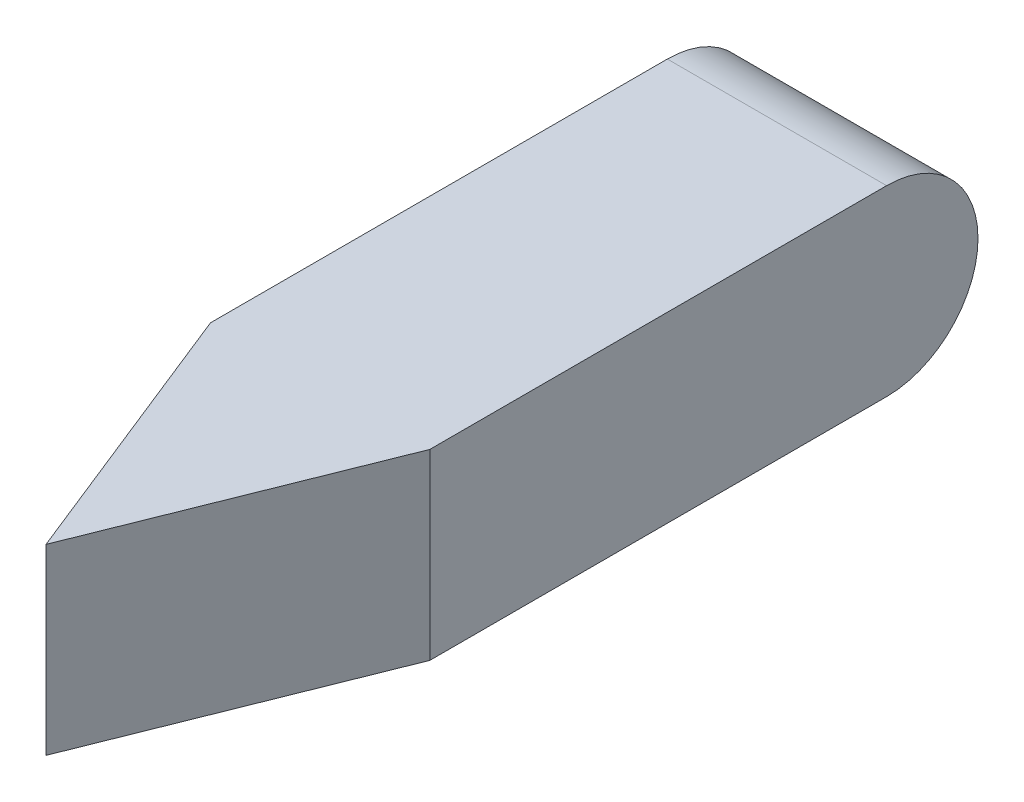
SolidWorks part; units mm, degrees
ref_plane "前视基准面" through (0, 0, 0) normal (0, 0, 1) x (1, 0, 0)
ref_plane "上视基准面" through (0, 0, 0) normal (0, 1, 0) x (1, 0, 0)
ref_plane "右视基准面" through (0, 0, 0) normal (1, 0, 0) x (0, 0, -1)
sketch "草图2" plane through (0, 0, 0) normal (0, 0, 1) x (1, 0, 0)
  line L1 (0, 0) -> (12, 0)
  line L2 (0, 0) -> (0, 10)
  line L3 (0, 10) -> (12, 10)
  line L4 (12, 0) -> (12, 10)
  dimension "D1" = 10
  dimension "D2" = 12
extrude "凸台-拉伸1" add sketch "草图2" along normal blind 45
sketch "草图3" plane through (12, 0, 0) normal (1, 0, 0) x (0, 0, -1)
  line L1 (-45, 10) -> (0, 10) construction
  line L3 (-45, 0) -> (0, 0) construction
  line L4 (0, 0) -> (0, 10) construction
  line L5 (-5, 10) -> (0, 10)
  line L6 (0, 10) -> (0, 0)
  line L7 (0, 0) -> (-5, 0)
  circle A1 centre (-5, 5) radius 5
  line M1 (0, 0) -> (0, 10)
  line M2 (0, 10) -> (-45, 10)
  line M4 (-45, 0) -> (0, 0)
extrude "切除-拉伸1" cut sketch "草图3" against normal blind 65 contours A1 M4 M1 | A1 L6 M2
sketch "草图4" plane through (0, 0, 0) normal (0, -1, 0) x (1, 0, 0)
  line L0 (0, 30) -> (0, 45)
  line L1 (0, 45) -> (0, 5) construction
  line L2 (0, 45) -> (6, 45)
  line L4 (6, 45) -> (12, 45)
  line L6 (12, 45) -> (12, 5) construction
  line L7 (0, 45) -> (12, 45) construction
  line L8 (12, 45) -> (12, 30)
  line L9 (12, 30) -> (6, 45)
  line L10 (0, 30) -> (6, 45)
  line M2 (0, 45) -> (0, 5)
  line M4 (12, 5) -> (12, 45)
  line M5 (12, 45) -> (0, 45)
  dimension "D1" = 15
  dimension "D2" = 6
  dimension "D3" = 15
extrude "切除-拉伸2" cut sketch "草图4" against normal blind 65 contours L10 M2 M5 | L9 M4 M5
